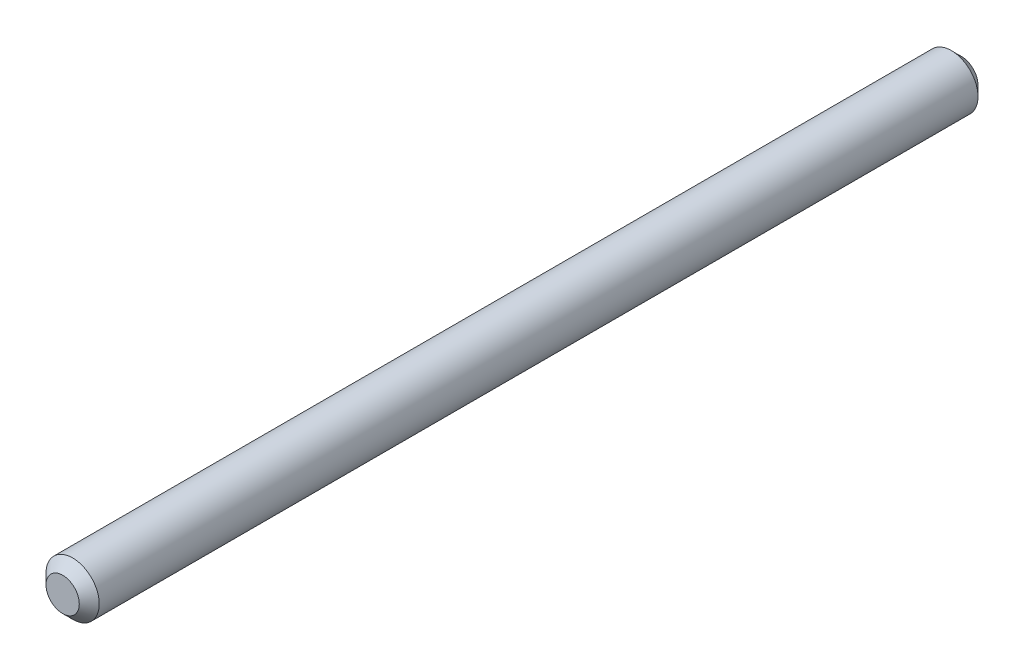
SolidWorks part; units mm, degrees
material "Alliage de zinc AC41A, brut"
ref_plane "Plan de face" through (0, 0, 0) normal (0, 0, 1) x (1, 0, 0)
ref_plane "Plan de dessus" through (0, 0, 0) normal (0, 1, 0) x (1, 0, 0)
ref_plane "Plan de droite" through (0, 0, 0) normal (1, 0, 0) x (0, 0, -1)
sketch "Esquisse1" plane through (0, 0, 0) normal (0, 0, 1) x (1, 0, 0)
  circle A0 centre (0, 0) radius 1
  dimension "D1" = 2
extrude "Boss.-Extru.1" add sketch "Esquisse1" along normal blind 33.75
chamfer "Chanfrein1" distance 0.375 angle 45 2 edges at (1, 0, 33.75) (1, 0, 0)
